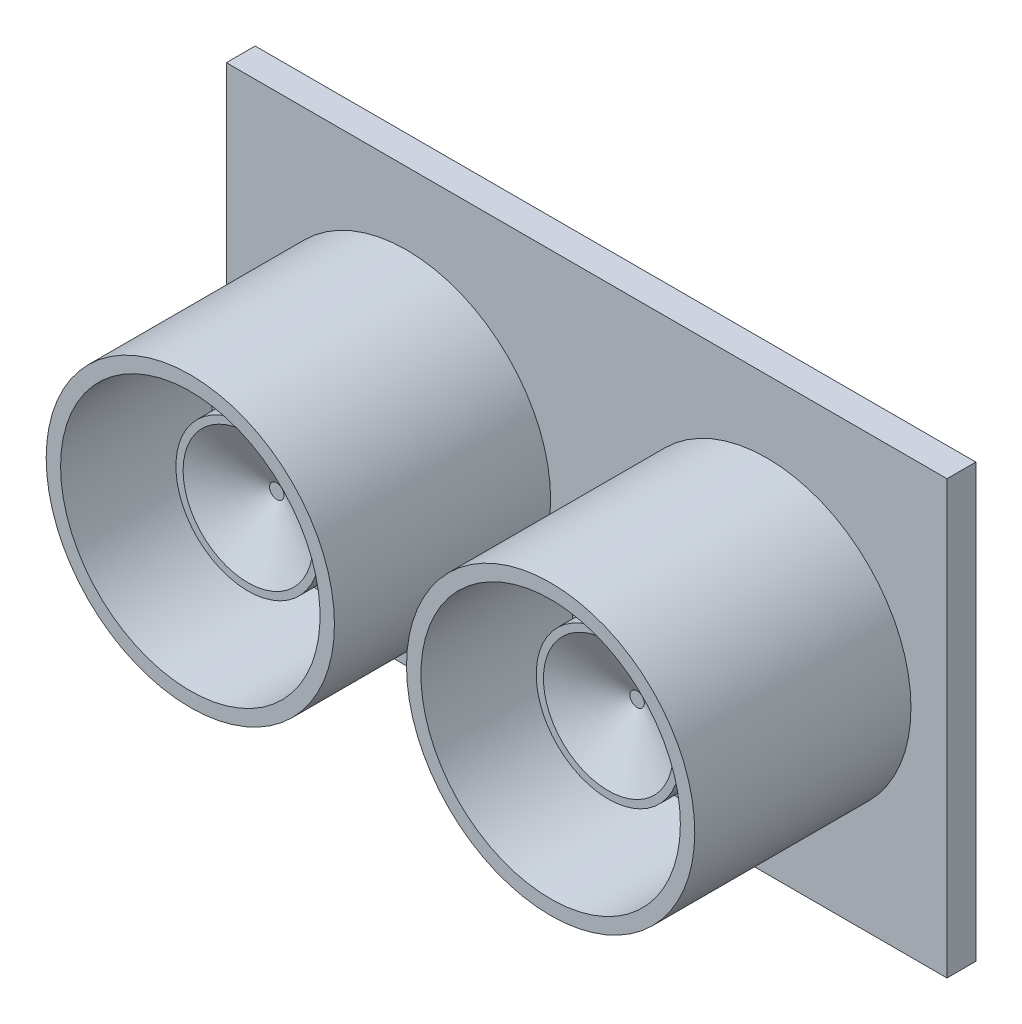
SolidWorks part; units mm, degrees
ref_plane "前视基准面" through (0, 0, 0) normal (0, 0, 1) x (1, 0, 0)
ref_plane "上视基准面" through (0, 0, 0) normal (0, 1, 0) x (1, 0, 0)
ref_plane "右视基准面" through (0, 0, 0) normal (1, 0, 0) x (0, 0, -1)
sketch "草图1" plane through (0, 0, 0) normal (0, 0, 1) x (1, 0, 0)
  line L1 (-25, -15) -> (25, -15)
  line L2 (-25, -15) -> (-25, 15)
  line L3 (-25, 15) -> (25, 15)
  line L4 (25, -15) -> (25, 15)
  line L5 (-25, -15) -> (25, 15) construction
  line L6 (-25, 15) -> (25, -15) construction
  point P0 (0, 0)
  dimension "D1" = 50
  dimension "D2" = 30
extrude "凸台-拉伸1" add sketch "草图1" along normal blind 2
sketch "草图2" plane through (0, 0, 2) normal (0, 0, 1) x (1, 0, 0)
  line L0 (0, 26.1848) -> (0, -24.8103) construction
  line L1 (-35.0422, 0) -> (36.428, 0) construction
  line L2 (25, -15) -> (25, 15) construction
  circle A0 centre (12.5, 0) radius 10
  circle A1 centre (-12.5, 0) radius 10
  circle A2 centre (12.5, 0) radius 9
  circle A3 centre (-12.5, 0) radius 9
  dimension "D2" = 20
  dimension "D3" = 18
  dimension "D1" = 12.5
extrude "凸台-拉伸2" add sketch "草图2" along normal blind 15
sketch "草图3" plane through (0, 0, 2) normal (0, 0, 1) x (1, 0, 0)
  circle A0 centre (-12.5, 0) radius 9 construction
  circle A1 centre (12.5, 0) radius 9 construction
  circle A2 centre (-12.5, 0) radius 9 construction
  circle A3 centre (12.5, 0) radius 9 construction
  circle A4 centre (12.5, 0) radius 7.5
  circle A5 centre (-12.5, 0) radius 7.5
  dimension "D1" = 15
  dimension "D2" = 15
extrude "凸台-拉伸3" add sketch "草图3" along normal blind 6
sketch "草图4" plane through (0, 0, 8) normal (0, 0, 1) x (1, 0, 0)
  circle A0 centre (-12.5, 0) radius 7.5 construction
  circle A1 centre (12.5, 0) radius 7.5 construction
  circle A2 centre (-12.5, 0) radius 7.5 construction
  circle A3 centre (12.5, 0) radius 7.5 construction
  circle A4 centre (-12.5, 0) radius 5
  circle A5 centre (12.5, 0) radius 5
  dimension "D1" = 10
  dimension "D2" = 10
extrude "凸台-拉伸4" add sketch "草图4" along normal blind 5
sketch "草图5" plane through (0, 0, 0) normal (0, 1, 0) x (1, 0, 0)
  line L0 (12.5, -13) -> (17, -13)
  line L2 (12.5, -14.4653) -> (12.5, -6.8544) construction
  line L3 (12.5, -11) -> (13, -11)
  line L6 (17, -13) -> (13, -11)
  line L7 (12.5, -13) -> (12.5, -11)
  dimension "D1" = 2
  dimension "D2" = 4.5
  dimension "D3" = 0.5
revolve "切除-旋转1" cut sketch "草图5" angle 360 about L2
mirror "镜向1" about plane through (0, 0, 0) normal (1, 0, 0) of "切除-旋转1"
sketch "草图6" plane through (0, 0, 17) normal (0, 0, 1) x (1, 0, 0)
  line L0 (-21.8205, -3.6232) -> (-10.4205, -9.7814)
  line L1 (-22.4791, -0.6461) -> (-7.2605, -8.867)
  line L2 (-22.28, 2.086) -> (-5.3938, -7.0358)
  line L3 (-21.6088, 4.1267) -> (-4.055, -5.3556)
  line L4 (-20.5792, 5.8929) -> (-3.1424, -3.5264)
  line L5 (-19.2116, 7.4131) -> (-2.6207, -1.5492)
  line L6 (-17.2162, 8.818) -> (-2.5397, 0.8899)
  line L7 (-14.6722, 9.7612) -> (-3.1455, 3.5346)
  line L8 (-11.4698, 9.9468) -> (-4.7459, 6.3146)
  line L9 (-13.0897, 9.9826) -> (-20.7919, -5.5897)
  line L10 (-16.4448, 9.189) -> (-22.1974, -2.4415)
  line L11 (-10.1419, 9.718) -> (-18.7926, -7.772)
  line L12 (-7.5908, 8.7121) -> (-16.4448, -9.189)
  line L13 (-5.3327, 6.9735) -> (-13.6927, -9.9286)
  line L14 (-3.9693, 5.2179) -> (-11.4698, -9.9468)
  line L15 (-3.1616, 2.8238) -> (-9.2329, -9.4512)
  line L16 (3.1771, -3.6597) -> (14.5771, -9.8179)
  line L17 (2.5185, -0.6826) -> (17.7372, -8.9035)
  line L18 (2.7176, 2.0495) -> (19.6038, -7.0723)
  line L19 (3.3888, 4.0902) -> (20.9426, -5.3921)
  line L20 (4.4184, 5.8564) -> (21.8552, -3.5628)
  line L21 (5.786, 7.3766) -> (22.3769, -1.5857)
  line L22 (7.7814, 8.7815) -> (22.458, 0.8534)
  line L23 (10.3254, 9.7247) -> (21.8521, 3.4981)
  line L24 (13.5278, 9.9103) -> (20.2517, 6.2781)
  line L25 (11.9079, 9.9461) -> (4.2058, -5.6262)
  line L26 (8.5528, 9.1525) -> (2.8003, -2.478)
  line L27 (14.8557, 9.6815) -> (6.205, -7.8085)
  line L28 (17.4068, 8.6756) -> (8.5528, -9.2255)
  line L29 (19.6649, 6.937) -> (11.305, -9.9651)
  line L30 (21.0284, 5.1814) -> (13.5278, -9.9833)
  line L31 (21.8361, 2.7873) -> (15.7647, -9.4877)
  circle A0 centre (-12.5, 0) radius 10 construction
  circle A1 centre (-12.5, 0) radius 10 construction
  point P70 (0, 0)
